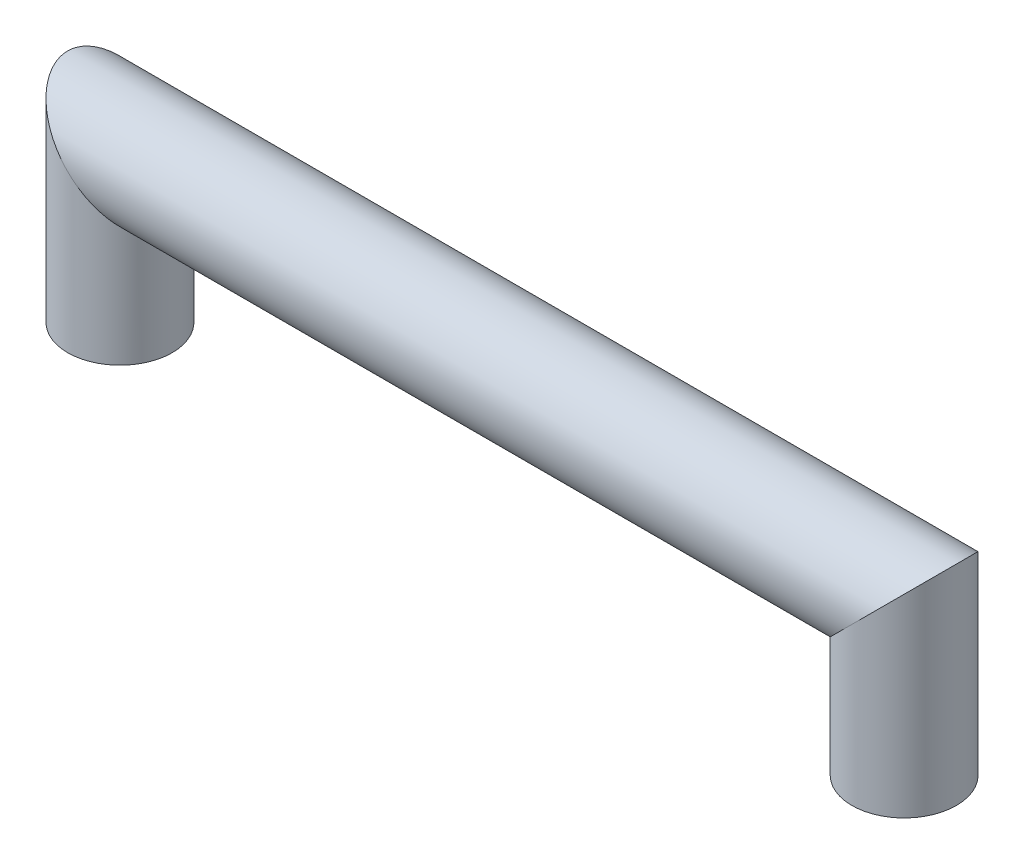
SolidWorks part; units mm, degrees
ref_plane "Front Plane" through (0, 0, 0) normal (0, 0, 1) x (1, 0, 0)
ref_plane "Top Plane" through (0, 0, 0) normal (0, 1, 0) x (1, 0, 0)
ref_plane "Right Plane" through (0, 0, 0) normal (1, 0, 0) x (0, 0, -1)
sketch "Sketch1" plane through (0, 0, 0) normal (0, 0, 1) x (1, 0, 0)
  line L0 (-7.5, 0) -> (-7.5, 3)
  line L1 (-7.5, 3) -> (7.5, 3)
  line L2 (7.5, 3) -> (7.5, 0)
  point P2 (0, 3)
  dimension "D1" = 15
  dimension "D2" = 3
sketch "Sketch2" plane through (0, 0, 0) normal (0, 1, 0) x (1, 0, 0)
  line L0 (-7.5, 0) -> (7.5, 0) construction
  circle A0 centre (-7.5, 0) radius 1
  dimension "D1" = 2
sweep "Sweep1" add profiles "Sketch2" path "Sketch1"
